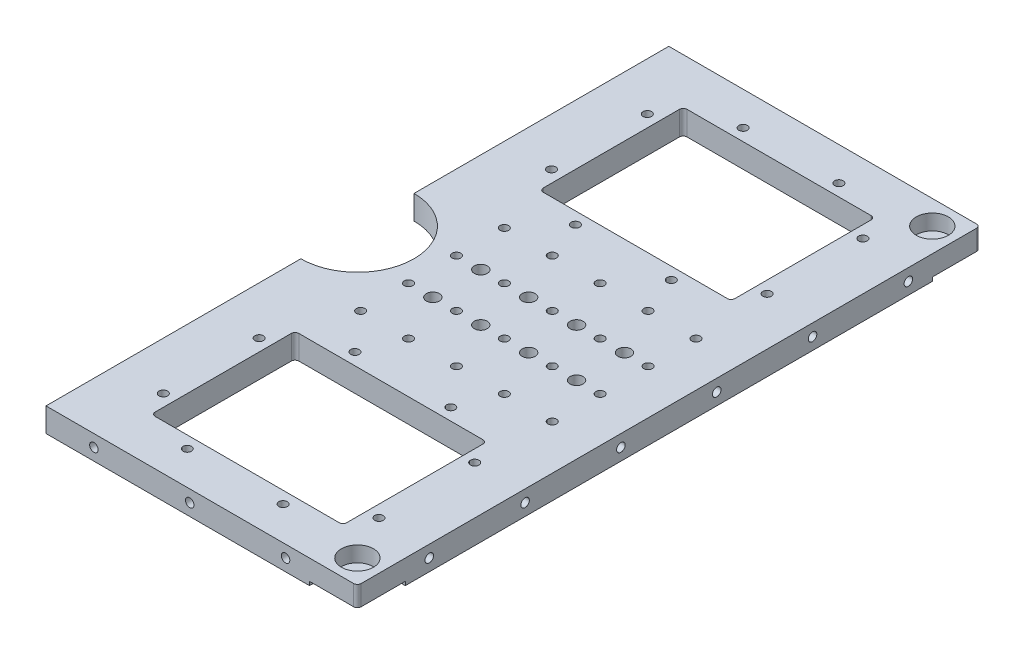
SolidWorks part; units mm, degrees
material "6061 Alloy"
ref_plane "Front Plane" through (0, 0, 0) normal (0, 0, 1) x (1, 0, 0)
ref_plane "Top Plane" through (0, 0, 0) normal (0, 1, 0) x (1, 0, 0)
ref_plane "Right Plane" through (0, 0, 0) normal (1, 0, 0) x (0, 0, -1)
sketch "Sketch1" plane through (0, 0, 0) normal (0, 1, 0) x (1, 0, 0)
  line L0 (0, -15) -> (0, -82.55)
  line L1 (0, 82.55) -> (82.55, 82.55)
  line L2 (0, 82.55) -> (0, 15)
  line L3 (0, -82.55) -> (82.55, -82.55)
  line L4 (82.55, 82.55) -> (82.55, -82.55)
  line L5 (0, 0) -> (82.55, 0) construction
  arc A0 (0, -15) -> (0, 15) centre (0, 0) ccw
  dimension "D1" = 15
  dimension "D2" = 82.55
  dimension "D3" = 165.1
extrude "Boss-Extrude1" add sketch "Sketch1" along normal blind 6.35
hole_wizard "#4-40 Tapped Hole - Z" positions "3DSketch1" profile "Sketch2" tap size "#4-40" standard "ANSI Inch"
sketch3d "3DSketch1"
  line L0 (82.55, 6.35, 82.55) -> (82.55, 6.35, -82.55) construction
  line L2 (82.55, 6.35, 82.55) -> (82.55, 0, 82.55) construction
  point P0 (82.55, 3.175, 63.5)
  dimension "D1" = 3.175
  dimension "D2" = 19.05
sketch "Sketch2" plane through (82.55, 3.175, 63.5) normal (0, 1, 0) x (0, 0, -1)
  line L0 (0, 0) -> (0, 8.2792)
  line L1 (0, 8.2792) -> (1.1303, 7.6)
  line L2 (1.1303, 7.6) -> (1.1303, 0)
  line L5 (1.1303, 0) -> (0, 0)
  line L10 (0, 8.2792) -> (-1.1303, 7.6) construction
  line L11 (0, -6.35) -> (0, 107.95) construction
  dimension "Tap Drill Dia." = 2.2606
  dimension "Tap Drill Depth" = 7.6
  dimension "Drill Angle" = 118
cosmetic thread "Hole Thread1" parameters "D1"=5.69, "D2"=2.8448
pattern_linear "LPattern1" count 6 spacing 25.4 along (0, 0, -1) of "#4-40 Tapped Hole - Z"
cosmetic thread "Hole Thread2" parameters "D1"=5.69, "D2"=2.8448
cosmetic thread "Hole Thread3" parameters "D1"=5.69, "D2"=2.8448
cosmetic thread "Hole Thread4" parameters "D1"=5.69, "D2"=2.8448
cosmetic thread "Hole Thread5" parameters "D1"=5.69, "D2"=2.8448
cosmetic thread "Hole Thread6" parameters "D1"=5.69, "D2"=2.8448
hole_wizard "#4-40 Tapped Hole - X" positions "3DSketch2" profile "Sketch3" tap size "#4-40" standard "ANSI Inch"
sketch3d "3DSketch2"
  line L0 (0, 6.35, 82.55) -> (82.55, 6.35, 82.55) construction
  line L1 (82.55, 6.35, 82.55) -> (82.55, 0, 82.55) construction
  point P0 (63.5, 3.175, 82.55)
  dimension "D1" = 3.175
  dimension "D2" = 19.05
sketch "Sketch3" plane through (63.5, 3.175, 82.55) normal (1, 0, 0) x (0, -1, 0)
  line L0 (0, 0) -> (0, 8.2792)
  line L1 (0, 8.2792) -> (1.1303, 7.6)
  line L2 (1.1303, 7.6) -> (1.1303, 0)
  line L5 (1.1303, 0) -> (0, 0)
  line L10 (0, 8.2792) -> (-1.1303, 7.6) construction
  line L11 (0, -6.35) -> (0, 107.95) construction
  dimension "Tap Drill Dia." = 2.2606
  dimension "Tap Drill Depth" = 7.6
  dimension "Drill Angle" = 118
cosmetic thread "Hole Thread7" parameters "D1"=5.69, "D2"=2.8448
pattern_linear "LPattern2" count 3 spacing 25.4 along (-1, 0, 0) of "#4-40 Tapped Hole - X"
cosmetic thread "Hole Thread8" parameters "D1"=5.69, "D2"=2.8448
cosmetic thread "Hole Thread9" parameters "D1"=5.69, "D2"=2.8448
ref_plane "Plane1" through (0, 0, 0) normal (0, 0, 1) x (1, 0, 0)
mirror "Mirror1" about plane through (0, 0, 0) normal (0, 0, 1) of "LPattern2", "#4-40 Tapped Hole - X"
cosmetic thread "Hole Thread10" parameters "D1"=5.69, "D2"=2.8448
cosmetic thread "Hole Thread11" parameters "D1"=5.69, "D2"=2.8448
cosmetic thread "Hole Thread12" parameters "D1"=5.69, "D2"=2.8448
sketch "Cu Flex cable mount dims" plane through (0, 0, 0) normal (0, 1, 0) x (1, 0, 0)
  line L0 (82.55, -82.55) -> (82.55, 82.55) construction
  arc A0 (0, -15) -> (0, 15) centre (0, 0) ccw construction
  point P0 (39.05, 6.35)
  point P1 (64.45, 6.35)
  point P2 (39.05, -6.35)
  point P3 (51.75, 6.35)
  point P4 (64.45, -6.35)
  point P7 (51.75, -6.35)
  point P8 (26.35, 6.35)
  point P9 (26.35, -6.35)
  point P17 (15, 0)
  dimension "D1" = 3
  dimension "D2" = 12.7
  dimension "D3" = 26.35
  dimension "D4" = 12.7
  dimension "D5" = 6.35
  dimension "D6" = 12.7
  dimension "D7" = 18.1
  dimension "D8" = 11.35
sketch "Sketch5" plane through (0, 0, 0) normal (0, 1, 0) x (1, 0, 0)
  line L1 (15.875, 70.5) -> (66.675, 70.5)
  line L2 (15.875, 70.5) -> (15.875, 32.4)
  line L3 (15.875, 32.4) -> (66.675, 32.4)
  line L4 (66.675, 70.5) -> (66.675, 32.4)
  line L9 (0, 82.55) -> (0, 15) construction
  line L10 (82.55, 82.55) -> (0, 82.55) construction
  line L11 (15, 0) -> (82.55, 0) construction
  line L12 (82.55, -82.55) -> (82.55, 82.55) construction
  line L13 (66.675, -70.5) -> (66.675, -32.4)
  line L14 (15.875, -32.4) -> (66.675, -32.4)
  line L15 (15.875, -70.5) -> (15.875, -32.4)
  line L16 (15.875, -70.5) -> (66.675, -70.5)
  arc A0 (0, -15) -> (0, 15) centre (0, 0) ccw construction
  point P8 (28.575, 76.85)
  point P10 (53.975, 76.85)
  point P11 (53.975, 26.05)
  point P12 (28.575, 26.05)
  point P13 (9.525, 51.45)
  point P14 (73.025, 51.45)
  point P15 (28.575, -76.85)
  point P16 (9.525, -51.45)
  point P17 (28.575, -26.05)
  point P18 (53.975, -26.05)
  point P19 (53.975, -76.85)
  point P20 (73.025, -51.45)
  point P21 (15.875, 51.45)
  dimension "D1" = 38.1
  dimension "D2" = 50.8
  dimension "D3" = 15.875
  dimension "D4" = 12.05
  dimension "D5" = 25.4
  dimension "D6" = 12.7
  dimension "D7" = 6.35
  dimension "D8" = 6.35
  dimension "D9" = 6.35
  dimension "D10" = 6.35
extrude "Feedthroughs" cut sketch "Sketch5" along normal up to surface (6.35 mm away) up to face at (30.0167, 6.35, 0)
hole_wizard "#4-40 Tapped Hole - Y" positions "3DSketch5" profile "Sketch7" tap size "#4-40" standard "ANSI Inch" end condition through all
sketch3d "3DSketch5"
  line L0 (66.675, 6.35, -70.5) -> (15.875, 6.35, -70.5) construction
  line L1 (66.675, 6.35, -32.4) -> (66.675, 6.35, -70.5) construction
  line L2 (15.875, 6.35, -32.4) -> (66.675, 6.35, -32.4) construction
  line L3 (15.875, 6.35, -70.5) -> (15.875, 6.35, -32.4) construction
  point P0 (53.975, 6.35, -73.675)
  point P2 (69.85, 6.35, -64.15)
  point P4 (53.975, 6.35, -29.225)
  point P6 (28.575, 6.35, -29.225)
  point P8 (12.7, 6.35, -64.15)
  point P10 (28.575, 6.35, -73.675)
  point P85 (12.7, 6.35, -38.75)
  point P87 (69.85, 6.35, -38.75)
  dimension "D7" = 6.35
  dimension "D4" = 3.175
  dimension "D1" = 25.4
  dimension "D2" = 25.4
  dimension "D3" = 3.175
  dimension "D5" = 3.175
  dimension "D6" = 3.175
  dimension "D8" = 12.7
sketch "Sketch7" plane through (53.975, 6.35, -73.675) normal (1, 0, 0) x (0, 0, 1)
  line L0 (0, 0) -> (0, 6.35)
  line L1 (0, 6.35) -> (1.1303, 6.35)
  line L2 (1.1303, 6.35) -> (1.1303, 0)
  line L5 (1.1303, 0) -> (0, 0)
  line L11 (0, -6.35) -> (0, 107.95) construction
  dimension "Thru Tap Drill Dia." = 2.2606
  dimension "Thru Tap Drill Depth" = 6.35
cosmetic thread "Hole Thread13" parameters "D2"=2.8448
cosmetic thread "Hole Thread14" parameters "D2"=2.8448
cosmetic thread "Hole Thread31" parameters "D2"=2.8448
cosmetic thread "Hole Thread32" parameters "D2"=2.8448
cosmetic thread "Hole Thread33" parameters "D2"=2.8448
cosmetic thread "Hole Thread34" parameters "D2"=2.8448
cosmetic thread "Hole Thread39" parameters "D2"=2.8448
cosmetic thread "Hole Thread40" parameters "D2"=2.8448
mirror "4-40 Tapped Hole - Y Mirror" about plane through (0, 0, 0) normal (0, 0, 1) of "#4-40 Tapped Hole - Y"
cosmetic thread "Hole Thread21" parameters "D2"=2.8448
cosmetic thread "Hole Thread23" parameters "D2"=2.8448
cosmetic thread "Hole Thread35" parameters "D2"=2.8448
cosmetic thread "Hole Thread36" parameters "D2"=2.8448
cosmetic thread "Hole Thread37" parameters "D2"=2.8448
cosmetic thread "Hole Thread38" parameters "D2"=2.8448
cosmetic thread "Hole Thread41" parameters "D2"=2.8448
cosmetic thread "Hole Thread42" parameters "D2"=2.8448
fillet "Fillet1" radius 1 8 edges at (15.875, 3.175, 70.5) (15.875, 3.175, 32.4) (66.675, 3.175, 70.5) (66.675, 3.175, 32.4) (15.875, 3.175, -32.4) (15.875, 3.175, -70.5) (66.675, 3.175, -32.4) (66.675, 3.175, -70.5)
hole_wizard "CBORE for #4 Socket Head Cap Screw1" positions "3DSketch6" profile "Sketch8" counterbore size "#4" standard "ANSI Inch"
sketch3d "3DSketch6"
  line L0 (82.55, 6.35, -82.55) -> (0, 6.35, -82.55) construction
  line L1 (82.55, 6.35, 82.55) -> (82.55, 6.35, -82.55) construction
  line L2 (0, 6.35, 82.55) -> (82.55, 6.35, 82.55) construction
  point P0 (76.2, 6.35, -76.2)
  point P2 (76.2, 6.35, 76.2)
  dimension "D2" = 6.35
  dimension "D1" = 6.35
  dimension "D3" = 6.35
  dimension "D4" = 6.35
sketch "Sketch8" plane through (76.2, 6.35, -76.2) normal (1, 0, 0) x (0, 0, 1)
  line L0 (0, 0) -> (0, 9.8706)
  line L1 (0, 9.8706) -> (1.6319, 8.89)
  line L2 (1.6319, 8.89) -> (1.6319, 4.1148)
  line L3 (1.6319, 4.1148) -> (4.2545, 4.1148)
  line L4 (4.2545, 4.1148) -> (4.2545, 0)
  line L5 (4.2545, 0) -> (0, 0)
  line L10 (0, 9.8706) -> (-1.632, 8.89) construction
  line L11 (0, -6.35) -> (0, 107.95) construction
  dimension "Hole Dia." = 3.2639
  dimension "Hole Depth" = 8.89
  dimension "C'Bore Dia." = 8.509
  dimension "C'Bore Depth" = 4.1148
  dimension "Drill Angle" = 118
hole_wizard "#8-32 Tapped Heat strap" positions "3DSketch7" profile "Sketch9" tap size "#8-32" standard "ANSI Inch" end condition through all
sketch3d "3DSketch7"
  point P0 (26.35, 6.35, -6.35)
  point P2 (39.05, 6.35, -6.35)
  point P4 (51.75, 6.35, -6.35)
  point P6 (64.45, 6.35, -6.35)
  point P8 (64.45, 6.35, 6.35)
  point P10 (51.75, 6.35, 6.35)
  point P12 (39.05, 6.35, 6.35)
  point P14 (26.35, 6.35, 6.35)
sketch "Sketch9" plane through (26.35, 6.35, -6.35) normal (1, 0, 0) x (0, 0, 1)
  line L0 (0, 0) -> (0, 6.35)
  line L1 (0, 6.35) -> (1.7272, 6.35)
  line L2 (1.7272, 6.35) -> (1.7272, 0)
  line L5 (1.7272, 0) -> (0, 0)
  line L11 (0, -6.35) -> (0, 107.95) construction
  dimension "Thru Tap Drill Dia." = 3.4544
  dimension "Thru Tap Drill Depth" = 6.35
cosmetic thread "Hole Thread43" parameters "D2"=4.1656
cosmetic thread "Hole Thread44" parameters "D2"=4.1656
cosmetic thread "Hole Thread45" parameters "D2"=4.1656
cosmetic thread "Hole Thread46" parameters "D2"=4.1656
cosmetic thread "Hole Thread47" parameters "D2"=4.1656
cosmetic thread "Hole Thread48" parameters "D2"=4.1656
cosmetic thread "Hole Thread49" parameters "D2"=4.1656
cosmetic thread "Hole Thread50" parameters "D2"=4.1656
hole_wizard "#4-40 Tapped Grid" positions "3DSketch8" profile "Sketch10" tap size "#4-40" standard "ANSI Inch" end condition through all
sketch3d "3DSketch8"
  line L7 (82.55, 6.35, 82.55) -> (82.55, 6.35, -82.55) construction
  line L8 (16.875, 6.35, -32.4) -> (65.675, 6.35, -32.4) construction
  point P0 (70.7, 6.35, -6.35)
  dimension "D2" = 26.05
  dimension "D1" = 11.85
sketch "Sketch10" plane through (70.7, 6.35, -6.35) normal (1, 0, 0) x (0, 0, 1)
  line L0 (0, 0) -> (0, 6.35)
  line L1 (0, 6.35) -> (1.1303, 6.35)
  line L2 (1.1303, 6.35) -> (1.1303, 0)
  line L5 (1.1303, 0) -> (0, 0)
  line L11 (0, -6.35) -> (0, 107.95) construction
  dimension "Thru Tap Drill Dia." = 2.2606
  dimension "Thru Tap Drill Depth" = 6.35
cosmetic thread "Hole Thread51" parameters "D2"=2.8448
pattern_linear "LPattern4" count 6 spacing 12.7 along (-1, 0, 0) count 3 spacing 12.7 along (0, 0, 1) skipping (5, 0), (5, 1), (5, 2) of "#4-40 Tapped Grid"
cosmetic thread "Hole Thread52" parameters "D2"=2.8448
cosmetic thread "Hole Thread53" parameters "D2"=2.8448
cosmetic thread "Hole Thread54" parameters "D2"=2.8448
cosmetic thread "Hole Thread55" parameters "D2"=2.8448
cosmetic thread "Hole Thread56" parameters "D2"=2.8448
cosmetic thread "Hole Thread57" parameters "D2"=2.8448
cosmetic thread "Hole Thread58" parameters "D2"=2.8448
cosmetic thread "Hole Thread59" parameters "D2"=2.8448
cosmetic thread "Hole Thread60" parameters "D2"=2.8448
cosmetic thread "Hole Thread61" parameters "D2"=2.8448
cosmetic thread "Hole Thread62" parameters "D2"=2.8448
cosmetic thread "Hole Thread63" parameters "D2"=2.8448
cosmetic thread "Hole Thread64" parameters "D2"=2.8448
cosmetic thread "Hole Thread65" parameters "D2"=2.8448
cosmetic thread "Hole Thread66" parameters "D2"=2.8448
cosmetic thread "Hole Thread67" parameters "D2"=2.8448
cosmetic thread "Hole Thread68" parameters "D2"=2.8448
cosmetic thread "Hole Thread69" parameters "D2"=2.8448
cosmetic thread "Hole Thread70" parameters "D2"=2.8448
cosmetic thread "Hole Thread71" parameters "D2"=2.8448
cosmetic thread "Hole Thread72" parameters "D2"=2.8448
cosmetic thread "Hole Thread73" parameters "D2"=2.8448
cosmetic thread "Hole Thread74" parameters "D2"=2.8448
cosmetic thread "Hole Thread75" parameters "D2"=2.8448
cosmetic thread "Hole Thread76" parameters "D2"=2.8448
cosmetic thread "Hole Thread77" parameters "D2"=2.8448
cosmetic thread "Hole Thread78" parameters "D2"=2.8448
cosmetic thread "Hole Thread79" parameters "D2"=2.8448
cosmetic thread "Hole Thread80" parameters "D2"=2.8448
pattern_linear "LPattern5" count 2 spacing 12.7 along (0, 0, -1) count 5 spacing 12.7 along (-1, 0, 0) skipping (0, 1), (0, 2), (0, 3), (0, 4) of "#4-40 Tapped Grid"
cosmetic thread "Hole Thread81" parameters "D2"=2.8448
cosmetic thread "Hole Thread82" parameters "D2"=2.8448
cosmetic thread "Hole Thread83" parameters "D2"=2.8448
cosmetic thread "Hole Thread84" parameters "D2"=2.8448
cosmetic thread "Hole Thread85" parameters "D2"=2.8448
sketch "Bar_cutouts" plane through (0, 0, 0) normal (0, 1, 0) x (1, 0, 0)
  line L0 (69.85, 82.55) -> (69.85, 69.85)
  line L1 (82.55, 82.55) -> (0, 82.55) construction
  line L2 (69.85, 69.85) -> (82.55, 69.85)
  line L3 (82.55, -82.55) -> (82.55, 82.55) construction
  line L4 (69.85, 82.55) -> (82.55, 82.55)
  line L5 (82.55, 82.55) -> (82.55, 69.85)
  line L6 (0, 0) -> (82.55, 0) construction
  line L7 (82.55, -82.55) -> (82.55, -69.85)
  line L8 (69.85, -82.55) -> (82.55, -82.55)
  line L9 (69.85, -82.55) -> (69.85, -69.85)
  line L10 (69.85, -69.85) -> (82.55, -69.85)
  circle A0 centre (69.85, 69.85) radius 1
  circle A1 centre (69.85, -69.85) radius 1
  dimension "D2" = 2
  dimension "D1" = 12.7
extrude "Cut-Extrude1" cut sketch "Bar_cutouts" along normal blind 1 contours A0 L2 L5 L4 L0 | L0 A0 L2 | A1 L9 L10 | L10 A1 L9 L8 L7 | L2 A0 L0 | A1 L10 L9
fillet "Fillet2" radius 1 2 edges at (82.55, 3.675, -82.55) (82.55, 3.675, 82.55)
equation "\"Width\"=82.55"
equation "\"D2@Sketch1\"=\"Width\""
equation "\"D3@Sketch5\"=(\"Width\"-\"D2@Sketch5\")/2"
equation "\"D4@Sketch5\"=(62.2-\"D1@Sketch5\")/2"
equation "\"D8@Sketch5\"=\"D7@Sketch5\""
equation "\"D9@Sketch5\"=\"D7@Sketch5\""
equation "\"D10@Sketch5\"=\"D9@Sketch5\""
equation "\"D2@3DSketch6\"=\"D1@3DSketch6\""
equation "\"D4@3DSketch6\"=\"D3@3DSketch6\""
equation "\"D4@3DSketch5\"=\"D3@3DSketch5\""
equation "\"D5@3DSketch5\"=\"D3@3DSketch5\""
equation "\"D6@3DSketch5\"=\"D3@3DSketch5\""
equation "\"D7@3DSketch5\"=(38.1-\"D2@3DSketch5\")/2"
equation "\"D8@3DSketch5\"=(50.8-\"D1@3DSketch5\")/2"
